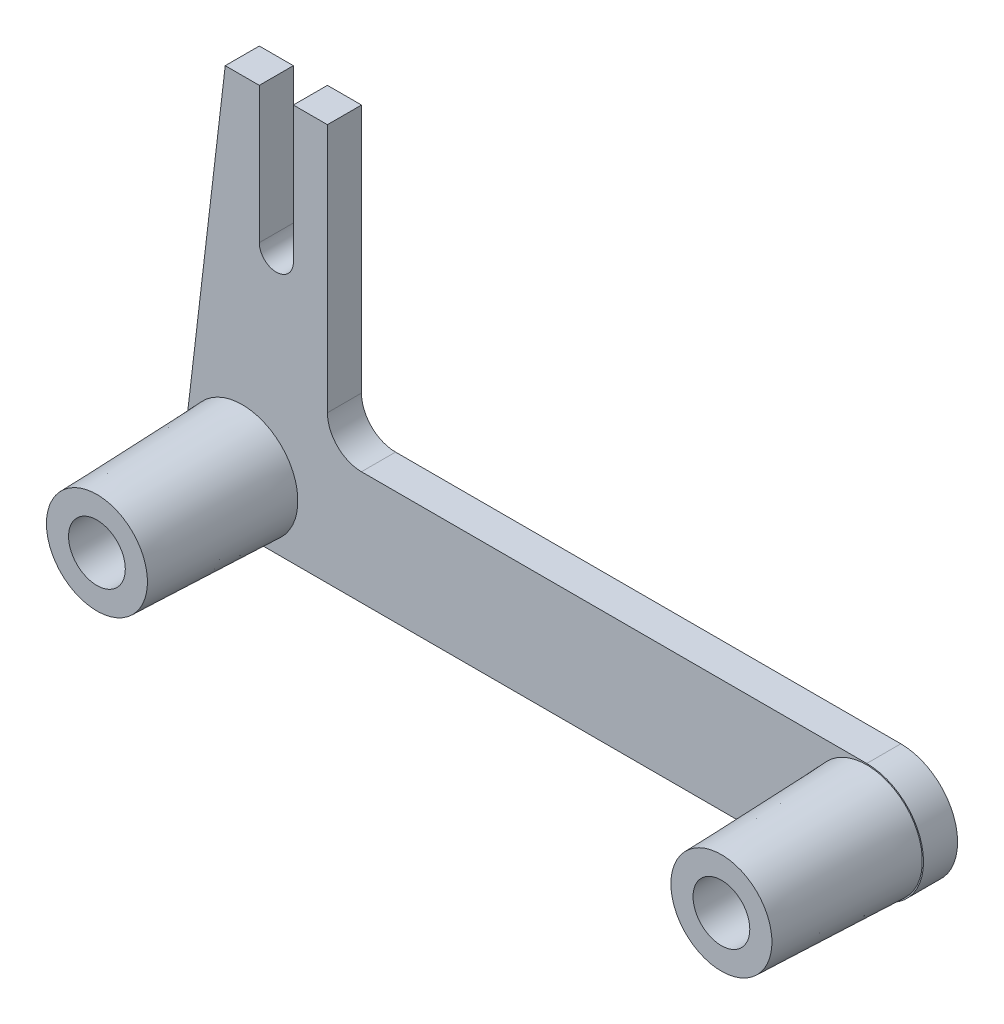
SolidWorks part; units mm, degrees
ref_plane "Plan1" through (0, 0, 0) normal (0, 0, 1) x (1, 0, 0)
ref_plane "Plan2" through (0, 0, 0) normal (0, 1, 0) x (1, 0, 0)
ref_plane "Plan3" through (0, 0, 0) normal (1, 0, 0) x (0, 0, -1)
sketch "Esquisse1" plane through (0, 0, 0) normal (0, 0, 1) x (1, 0, 0)
  line L0 (0.6788, -3.1164) -> (55.15, -3.1164)
  line L1 (-6.6527, 1.8836) -> (61.3509, 1.8836) construction
  line L2 (55.15, 6.8836) -> (10.65, 6.8836)
  line L3 (7.65, 9.8836) -> (7.65, 31.8556)
  line L4 (7.65, 31.8556) -> (4.65, 31.8556)
  line L5 (4.65, 31.8556) -> (4.65, 19.8556)
  line L6 (1.65, 19.8556) -> (1.65, 31.8556)
  line L7 (1.65, 31.8556) -> (-1.35, 31.8556)
  line L8 (-1.35, 31.8556) -> (-4.8157, 2.4406)
  line L9 (55.15, 1.8836) -> (55.15, -15.283) construction
  line L10 (0.15, 1.8556) -> (0.15, -13.4228) construction
  line L11 (3.15, 39.9053) -> (3.15, 14.4814) construction
  arc A0 (-4.8157, 2.4406) -> (0.6788, -3.1164) centre (0.15, 1.8556) ccw
  arc A1 (55.15, -3.1164) -> (55.15, 6.8836) centre (55.15, 1.8836) ccw
  arc A2 (1.65, 19.8556) -> (4.65, 19.8556) centre (3.15, 19.8556) ccw
  arc A3 (10.65, 6.8836) -> (7.65, 9.8836) centre (10.65, 9.8836) cw
  dimension "D1" = 3
  dimension "D4" = 5
  dimension "D5" = 5
  dimension "D2" = 55
  dimension "D3" = 3
  dimension "D6" = 18
  dimension "D7" = 30
  dimension "D8" = 3
  dimension "D9" = 3
  dimension "D10" = 3
  dimension "D11" = 30
extrude "Base-Extrusion" add sketch "Esquisse1" along normal blind 3
sketch "Esquisse3" plane through (0, 0, 0) normal (0, 0, -1) x (-1, 0, 0)
  circle A0 centre (-0.15, 1.8556) radius 5
  circle A1 centre (-55.15, 1.8836) radius 5
  dimension "D1" = 10
  dimension "D2" = 10
extrude "Boss.-Extru.1" add sketch "Esquisse3" against normal blind 15.8 draft 2
hole_wizard "Perçage1" positions "Esquisse12" profile "Esquisse11"
sketch "Esquisse12" plane through (0, 0, 15.8) normal (0, 0, 1) x (1, 0, 0)
  point P0 (55.15, 1.8836)
sketch "Esquisse11" plane through (55.15, 1.8836, 15.8) normal (1, 0, 0) x (0, -1, 0)
  line L0 (0, 0) -> (0, 17.3022)
  line L1 (0, 17.3022) -> (2.5, 15.8)
  line L2 (2.5, 15.8) -> (2.5, 0)
  line L4 (2.5, 0) -> (0, 0)
  line L6 (0, 17.3022) -> (-2.5, 15.8) construction
  line L7 (0, -4.2442) -> (0, 117.3081) construction
  dimension "Diamètre" = 5
  dimension "Profondeur" = 15.8
  dimension "Angle" = 118
hole_wizard "Perçage3" positions "Esquisse16" profile "Esquisse15"
sketch "Esquisse16" plane through (0, 0, 15.8) normal (0, 0, 1) x (1, 0, 0)
  point P0 (0.15, 1.8556)
sketch "Esquisse15" plane through (0.15, 1.8556, 15.8) normal (1, 0, 0) x (0, -1, 0)
  line L0 (0, 0) -> (0, 17.3022)
  line L1 (0, 17.3022) -> (2.5, 15.8)
  line L2 (2.5, 15.8) -> (2.5, 0)
  line L4 (2.5, 0) -> (0, 0)
  line L6 (0, 17.3022) -> (-2.5, 15.8) construction
  line L7 (0, -4.2442) -> (0, 117.3081) construction
  dimension "Diamètre" = 5
  dimension "Profondeur" = 15.8
  dimension "Angle" = 118
